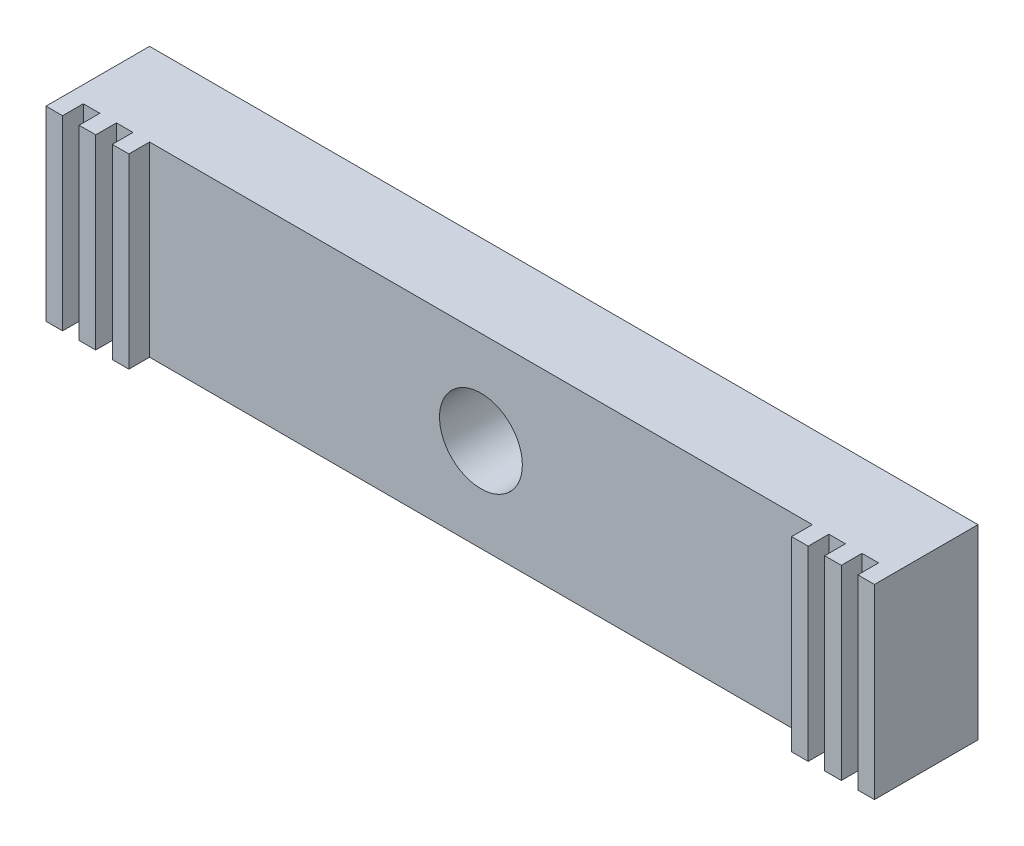
SolidWorks part; units mm, degrees
ref_plane "前视基准面" through (0, 0, 0) normal (0, 0, 1) x (1, 0, 0)
ref_plane "上视基准面" through (0, 0, 0) normal (0, 1, 0) x (1, 0, 0)
ref_plane "右视基准面" through (0, 0, 0) normal (1, 0, 0) x (0, 0, -1)
sketch "草图1" plane through (0, 0, 0) normal (0, 0, 1) x (1, 0, 0)
  line L1 (-20, 4.5) -> (20, 4.5)
  line L2 (-20, 4.5) -> (-20, -4.5)
  line L3 (-20, -4.5) -> (20, -4.5)
  line L4 (20, 4.5) -> (20, -4.5)
  circle A0 centre (0, 0) radius 2
  dimension "D5" = 4
  dimension "D1" = 9
  dimension "D2" = 40
  dimension "D3" = 20
  dimension "D4" = 4.5
extrude "凸台-拉伸1" add sketch "草图1" along normal blind 4
sketch "草图2" plane through (0, 0, 4) normal (0, 0, 1) x (1, 0, 0)
  line L0 (-19.2, 4.5) -> (-19.2, -4.5)
  line L1 (-18.4, 4.5) -> (-18.4, -4.5)
  line L2 (-17.6, 4.5) -> (-17.6, -4.5)
  line L3 (-16.8, 4.5) -> (-16.8, -4.5)
  line L4 (-20, 4.5) -> (-20, -4.5)
  line L5 (-20, 4.5) -> (-20, -4.5) construction
  line L7 (20, 4.5) -> (-20, 4.5) construction
  line L12 (-16, 4.5) -> (-16, -4.5)
  line L14 (-20, -4.5) -> (-19.2, -4.5)
  line L15 (-19.2, 4.5) -> (-20, 4.5)
  line L16 (-18.4, 4.5) -> (-17.6, 4.5)
  line L17 (-18.4, -4.5) -> (-17.6, -4.5)
  line L18 (-16.8, 4.5) -> (-16, 4.5)
  line L19 (-16.8, -4.5) -> (-16, -4.5)
  line L20 (16.8, 4.5) -> (16.8, -4.5)
  line L21 (17.6, 4.5) -> (17.6, -4.5)
  line L22 (18.4, 4.5) -> (18.4, -4.5)
  line L23 (19.2, 4.5) -> (19.2, -4.5)
  line L24 (16, 4.5) -> (16, -4.5)
  line L25 (20, 4.5) -> (20, -4.5)
  line L26 (16, -4.5) -> (16.8, -4.5)
  line L27 (16.8, 4.5) -> (16, 4.5)
  line L28 (17.6, 4.5) -> (18.4, 4.5)
  line L29 (17.6, -4.5) -> (18.4, -4.5)
  line L30 (19.2, 4.5) -> (20, 4.5)
  line L31 (19.2, -4.5) -> (20, -4.5)
  line L32 (20, -4.5) -> (20, 4.5) construction
  line L33 (-20, -4.5) -> (20, -4.5) construction
  point P28 (0, 0)
  dimension "D2" = 9
  dimension "D3" = 0.8
  dimension "D4" = 0.8
  dimension "D5" = 0.8
  dimension "D6" = 0.8
  dimension "D1" = 0.8
  dimension "D7" = 0
  dimension "D8" = 0
  dimension "D9" = 0.8
  dimension "D10" = 0.8
  dimension "D11" = 0.8
  dimension "D12" = 0.8
  dimension "D13" = 0.8
  dimension "D14" = 9
extrude "凸台-拉伸2" add sketch "草图2" along normal blind 1
